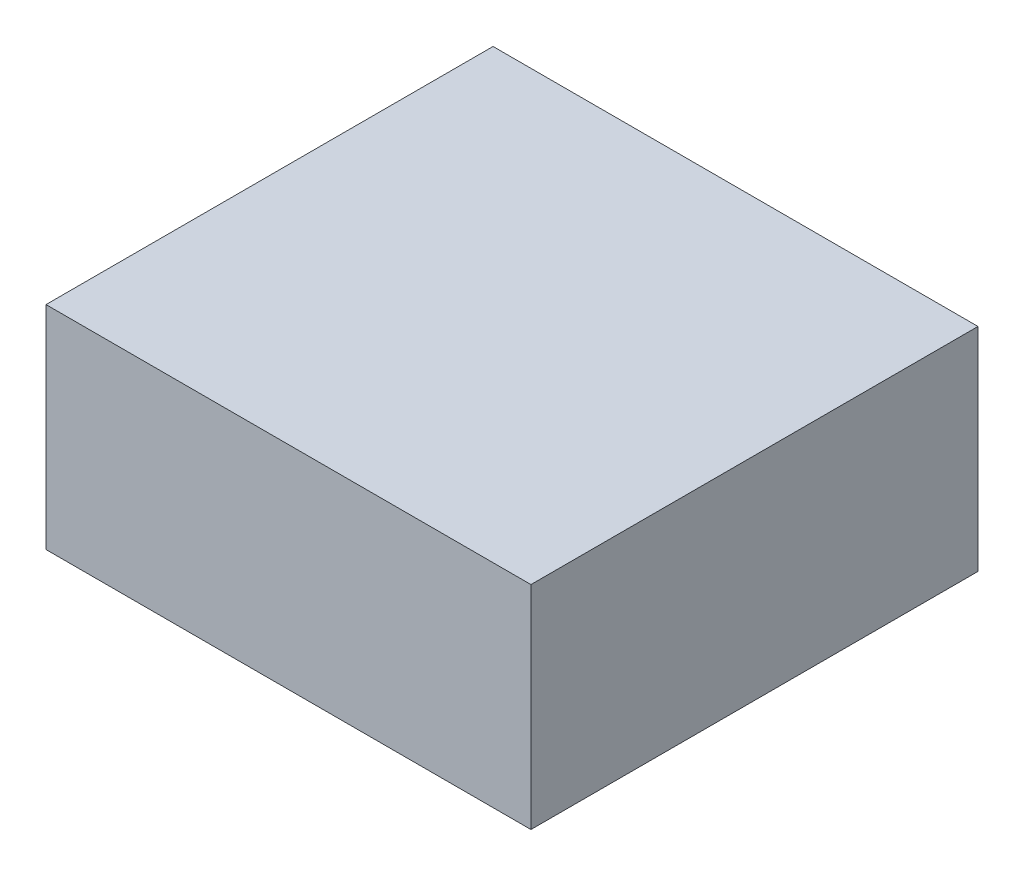
SolidWorks part; units mm, degrees
ref_plane "Front Plane" through (0, 0, 0) normal (0, 0, 1) x (1, 0, 0)
ref_plane "Top Plane" through (0, 0, 0) normal (0, 1, 0) x (1, 0, 0)
ref_plane "Right Plane" through (0, 0, 0) normal (1, 0, 0) x (0, 0, -1)
sketch "Sketch1" plane through (0, 0, 0) normal (0, 1, 0) x (1, 0, 0)
  line L1 (0, 0) -> (64, 0)
  line L2 (0, 0) -> (0, 59)
  line L3 (0, 59) -> (64, 59)
  line L4 (64, 0) -> (64, 59)
  dimension "D1" = 64
  dimension "D2" = 59
extrude "Boss-Extrude1" add sketch "Sketch1" along normal blind 28
